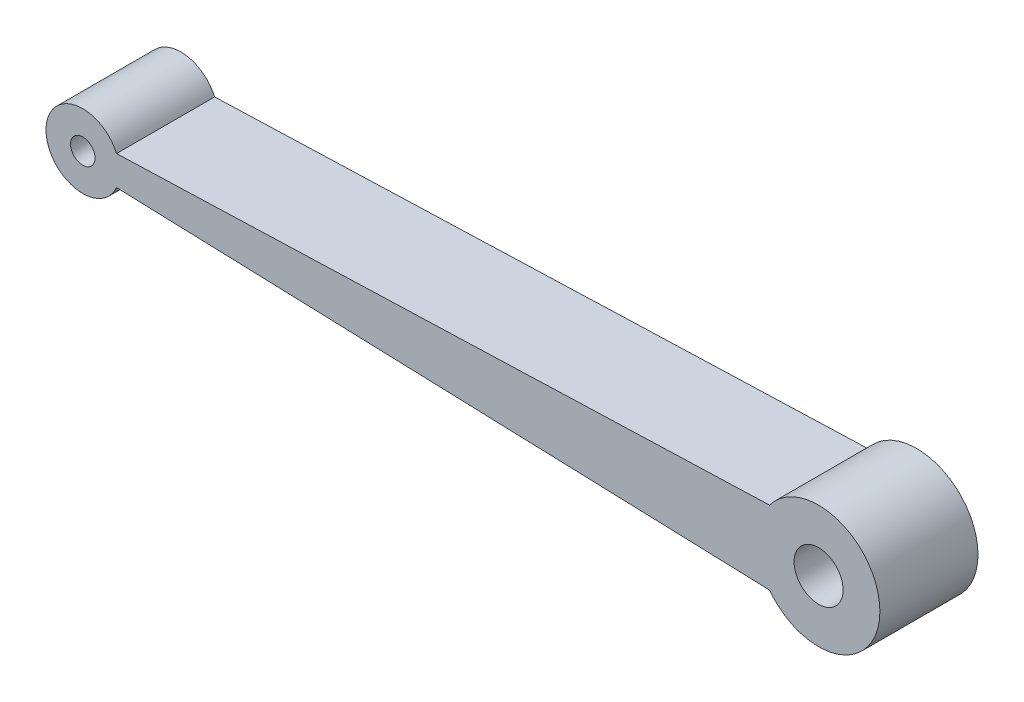
SolidWorks part; units mm, degrees
ref_plane "Front Plane" through (0, 0, 0) normal (0, 0, 1) x (1, 0, 0)
ref_plane "Top Plane" through (0, 0, 0) normal (0, 1, 0) x (1, 0, 0)
ref_plane "Right Plane" through (0, 0, 0) normal (1, 0, 0) x (0, 0, -1)
sketch "Sketch3" plane through (0, 0, 0) normal (0, 0, 1) x (1, 0, 0)
  line L0 (0, 0) -> (150, 0) construction
  line L1 (6.8739, 3) -> (140, 7.5)
  line L2 (6.8739, -3) -> (140, -7.5)
  circle A0 centre (0, 0) radius 2.5
  arc A1 (6.8739, 3) -> (6.8739, -3) centre (0, 0) ccw
  circle A2 centre (150, 0) radius 5
  arc A3 (140, -7.5) -> (140, 7.5) centre (150, 0) ccw
  dimension "D1" = 5
  dimension "D2" = 15
  dimension "D4" = 10
  dimension "D5" = 25
  dimension "D3" = 150
  dimension "D6" = 7.5
  dimension "D7" = 3
extrude "Boss-Extrude2" add sketch "Sketch3" along normal mid plane 20
